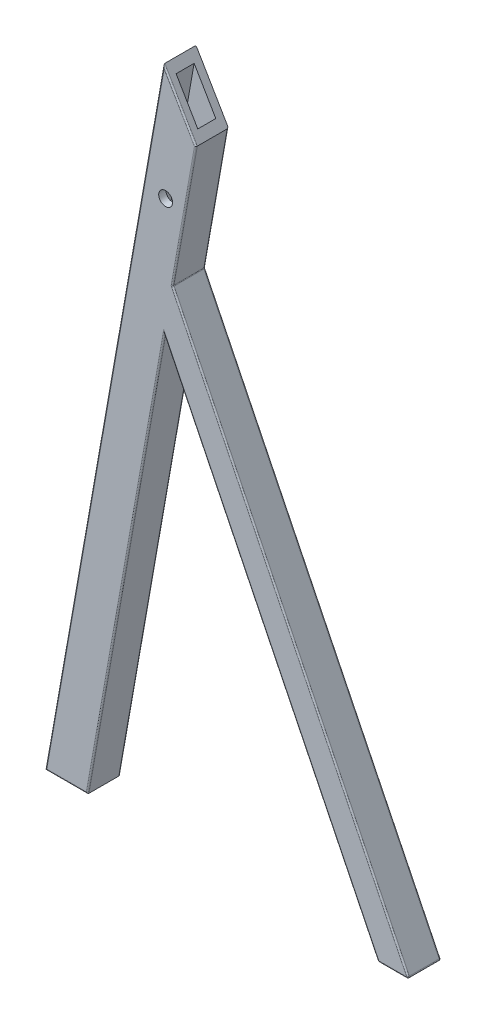
SolidWorks part; units mm, degrees
material "1023 Carbon Steel Sheet (SS)"
ref_plane "Ön Düzlem" through (0, 0, 0) normal (0, 0, 1) x (1, 0, 0)
ref_plane "Üst Düzlem" through (0, 0, 0) normal (0, 1, 0) x (1, 0, 0)
ref_plane "Sağ Düzlem" through (0, 0, 0) normal (1, 0, 0) x (0, 0, -1)
sketch "Sketch1" plane through (0, 0, 0) normal (0, 0, 1) x (1, 0, 0)
  line L0 (0, 0) -> (-209.4501, 0) construction
  line L1 (0, 0) -> (-154.0336, 314.2828)
  line L3 (-148.1406, 347.7036) -> (22.2729, 0)
  line L5 (0, 0) -> (22.2729, 0)
  line L7 (-154.0336, 314.2828) -> (-148.1406, 347.7036)
  line L8 (-209.4501, 0) -> (-131.3084, 443.1635)
  line L10 (-154.7181, 483.1635) -> (-239.9129, 0)
  line L11 (-239.9129, 0) -> (-209.4501, 0)
  line L12 (-131.3084, 443.1635) -> (-154.7181, 483.1635)
  point P3 (0, 0)
  point P10 (0, 0)
  dimension "D1" = 63.89
  dimension "D2" = 350
  dimension "D3" = 20
  dimension "D5" = 80
  dimension "D6" = 30
  dimension "D7" = 450
  dimension "D8" = 40
extrude "Boss-Extrude2" add sketch "Sketch1" along normal mid plane 23.5 contours L7 L1 L5 L3 | L10 L11 L8 L12
ref_plane "Plane1" through (0, 0, 0) normal (0, 0, 1) x (1, 0, 0)
sketch "Sketch2" plane through (0, 0, 0) normal (0, 0, 1) x (1, 0, 0)
  line L0 (-234.4831, 2) -> (-214.1746, 2)
  line L1 (-214.1746, 2) -> (-126.0111, 502)
  line L2 (-126.0111, 502) -> (-139.2665, 542)
  line L3 (-139.2665, 542) -> (-234.4831, 2)
  line L4 (-209.4501, 0) -> (-154.0336, 314.2828) construction
  line L5 (-154.7181, 483.1635) -> (-239.9129, 0) construction
  point P2 (-111.3598, 462.1618)
  point P5 (-108.0796, 424.0779)
  dimension "D1" = 5
  dimension "D2" = 5
  dimension "D3" = 500
  dimension "D4" = 40
  dimension "D5" = 20
  dimension "D6" = 2
extrude "Cut-Extrude1" cut sketch "Sketch2" against normal mid plane 13
sketch "Sketch3" plane through (0, 0, 11.75) normal (0, 0, 1) x (1, 0, 0)
  line L0 (-148.1406, 347.7036) -> (-131.3084, 443.1635) construction
  circle A0 centre (-153.1353, 400) radius 5
  dimension "D1" = 10
  dimension "D2" = 14
  dimension "D3" = 400
extrude "Cut-Extrude2" cut sketch "Sketch3" against normal through all
fillet "Fillet2" radius 1 17 edges at (-62.9338, 173.8518, -11.75) (11.1365, 0, 11.75) (-77.0168, 157.1414, 11.75) (-181.7418, 157.1414, 11.75) (-224.6815, 0, 11.75) (-197.3155, 241.5817, 11.75) (-143.0133, 463.1635, 11.75) (-139.7245, 395.4336, 11.75) (-62.9338, 173.8518, 11.75) (11.1365, 0, -11.75) (-77.0168, 157.1414, -11.75) (0, 0, 0) (22.2729, 0, 0) (-148.1406, 347.7036, 0) (-181.7418, 157.1414, -11.75) (-197.3155, 241.5817, -11.75) (-139.7245, 395.4336, -11.75)
